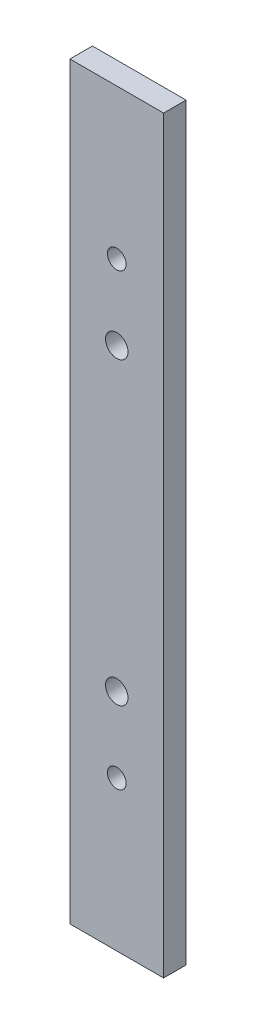
SolidWorks part; units mm, degrees
ref_plane "Front Plane" through (0, 0, 0) normal (0, 0, 1) x (1, 0, 0)
ref_plane "Top Plane" through (0, 0, 0) normal (0, 1, 0) x (1, 0, 0)
ref_plane "Right Plane" through (0, 0, 0) normal (1, 0, 0) x (0, 0, -1)
sketch "Sketch1" plane through (0, 0, 0) normal (0, 0, 1) x (1, 0, 0)
  line L1 (-12.5, -100) -> (12.5, -100)
  line L2 (-12.5, -100) -> (-12.5, 100)
  line L3 (-12.5, 100) -> (12.5, 100)
  line L4 (12.5, -100) -> (12.5, 100)
  line L5 (-12.5, -100) -> (12.5, 100) construction
  line L6 (-12.5, 100) -> (12.5, -100) construction
  point P0 (0, 0)
  dimension "D1" = 200
  dimension "D2" = 25
extrude "Boss-Extrude1" add sketch "Sketch1" along normal blind 6
sketch "Sketch2" plane through (0, 0, 6) normal (0, 0, 1) x (1, 0, 0)
  line L0 (0, 100) -> (0, -100) construction
  line L1 (-12.5, -100) -> (12.5, -100) construction
  line L2 (-12.5, 100) -> (-12.5, -100) construction
  line L3 (12.5, 0) -> (-12.5, 0) construction
  line L4 (12.5, -100) -> (12.5, 100) construction
  circle A1 centre (0, -60) radius 2.5
  circle A2 centre (0, 60) radius 2.5
  circle A3 centre (0, -40) radius 3
  circle A4 centre (0, 40) radius 3
  dimension "D1" = 6
  dimension "D2" = 5
  dimension "D3" = 40
  dimension "D4" = 12.5
  dimension "D5" = 12.5
  dimension "D6" = 60
extrude "Cut-Extrude1" cut sketch "Sketch2" against normal blind 6
